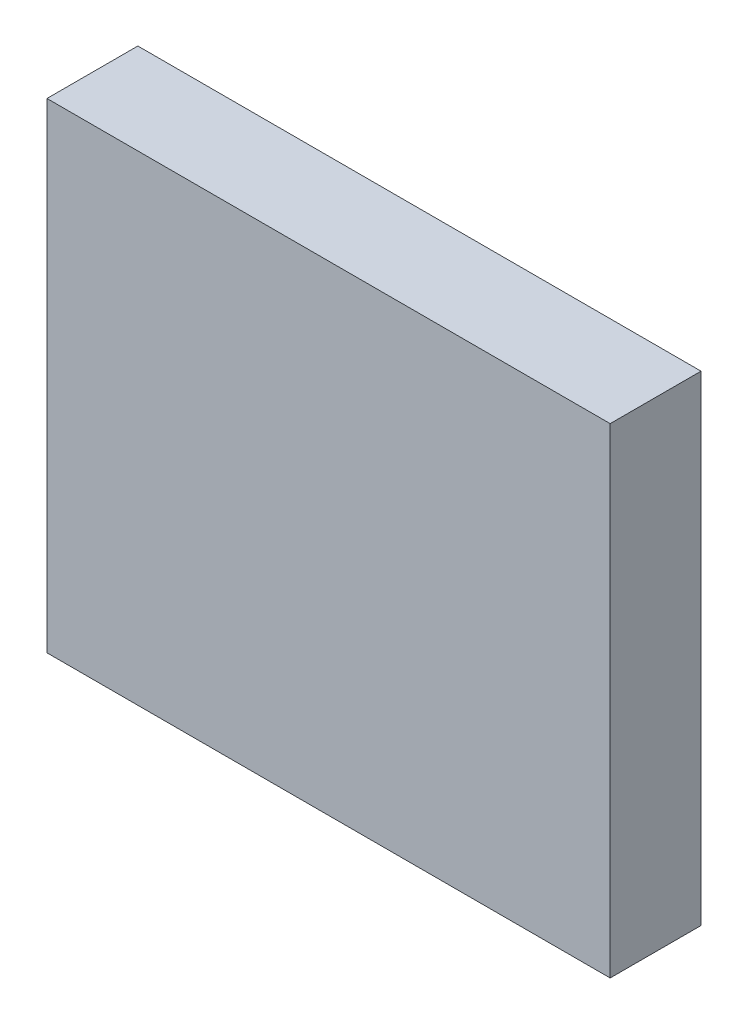
SolidWorks part; units mm, degrees
ref_plane "Front Plane" through (0, 0, 0) normal (0, 0, 1) x (1, 0, 0)
ref_plane "Top Plane" through (0, 0, 0) normal (0, 1, 0) x (1, 0, 0)
ref_plane "Right Plane" through (0, 0, 0) normal (1, 0, 0) x (0, 0, -1)
sketch "Sketch1" plane through (0, 0, 0) normal (0, 0, 1) x (1, 0, 0)
  line L0 (-3.0988, 2.6416) -> (3.0988, 2.6416)
  line L1 (3.0988, 2.6416) -> (3.0988, -2.6416)
  line L2 (3.0988, -2.6416) -> (-3.0988, -2.6416)
  line L3 (-3.0988, -2.6416) -> (-3.0988, 2.6416)
extrude "Component_Outline" add sketch "Sketch1" along normal blind 1 separate body
sketch3d "3DSketch1"
  line L0 (0, 0, 0) -> (1, 0, 0)
  line L1 (0, 0, 0) -> (0, 1, 0)
  line L2 (0, 0, 0) -> (0, 0, 1)
  point P0 (0, 0, 0)
